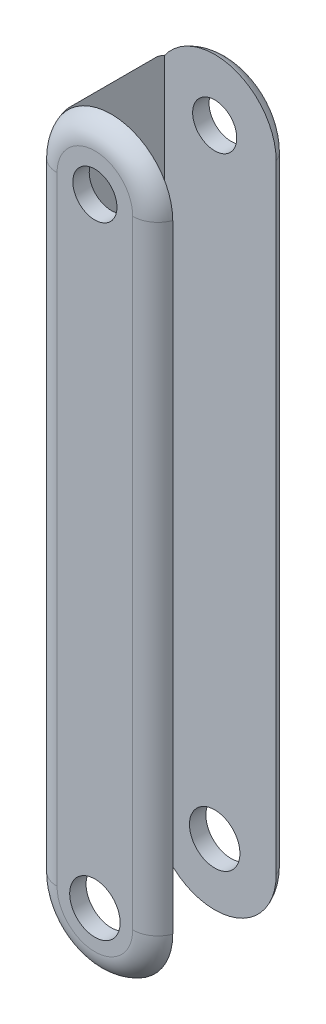
SolidWorks part; units mm, degrees
ref_plane "Face" through (0, 0, 0) normal (0, 0, 1) x (1, 0, 0)
ref_plane "Dessus" through (0, 0, 0) normal (0, 1, 0) x (1, 0, 0)
ref_plane "Droite" through (0, 0, 0) normal (1, 0, 0) x (0, 0, -1)
sketch "Esquisse1" plane through (0, 0, 0) normal (0, 0, 1) x (1, 0, 0)
  line L0 (0, 49) -> (0, 0)
  line L1 (10, 0) -> (10, 49)
  arc A0 (10, 0) -> (0, 0) centre (5, 0) cw
  arc A1 (10, 49) -> (0, 49) centre (5, 49) ccw
  dimension "D1" = 10
  dimension "D2" = 49
extrude "Base-Extrusion" add sketch "Esquisse1" along normal blind 10.8
fillet "Congé1" radius 2 4 edges at (5, -5, 10.8) (10, 24.5, 10.8) (5, 54, 10.8) (0, 24.5, 10.8)
fillet "Congé3" radius 2 4 edges at (10, 24.5, 0) (5, -5, 0) (0, 24.5, 0) (5, 54, 0)
sketch "Esquisse6" plane through (10, 0, 0) normal (1, 0, 0) x (0, 0, -1)
  line L0 (-9.5, 58.0141) -> (-9.5, -9.3539)
  line L2 (-9.5, -9.3539) -> (-1.3, -9.3539)
  line L3 (-1.3, -9.3539) -> (-1.3, 56.5487)
  line L4 (-1.3, 56.5487) -> (-9.5, 58.0141)
  line L5 (0, 49) -> (0, 0) construction
  line L8 (-10.8, 0) -> (-10.8, 49) construction
  dimension "D1" = 1.3
  dimension "D2" = 1.3
extrude "Enlèv. mat.-Extru.4" cut sketch "Esquisse6" against normal blind 9
sketch "Esquisse7" plane through (0, 0, 0) normal (-1, 0, 0) x (0, 0, 1)
  line L0 (9.5, -4.6009) -> (9.5, 5.4591)
  line L1 (9.5, 5.4591) -> (1.3, 5.4591)
  line L2 (1.3, 5.4591) -> (1.3, -4.6009)
  line L3 (1.3, -4.8735) -> (1.3, 0) construction
  line L4 (1.3, -4.6009) -> (9.5, -4.6009)
  dimension "D1" = 10.06
extrude "Enlèv. mat.-Extru.5" cut sketch "Esquisse7" against normal blind 9
sketch "Esquisse8" plane through (0, 0, 0) normal (0, 0, -1) x (-1, 0, 0)
  circle A0 centre (-5, 0) radius 2
  arc A1 (-9.8735, 0) -> (-0.1265, 0) centre (-5, 0) ccw construction
  circle A2 centre (-5, 49) radius 1.75
  dimension "D1" = 4
  dimension "D2" = 3.5
extrude "Enlèv. mat.-Extru.6" cut sketch "Esquisse8" against normal through all
